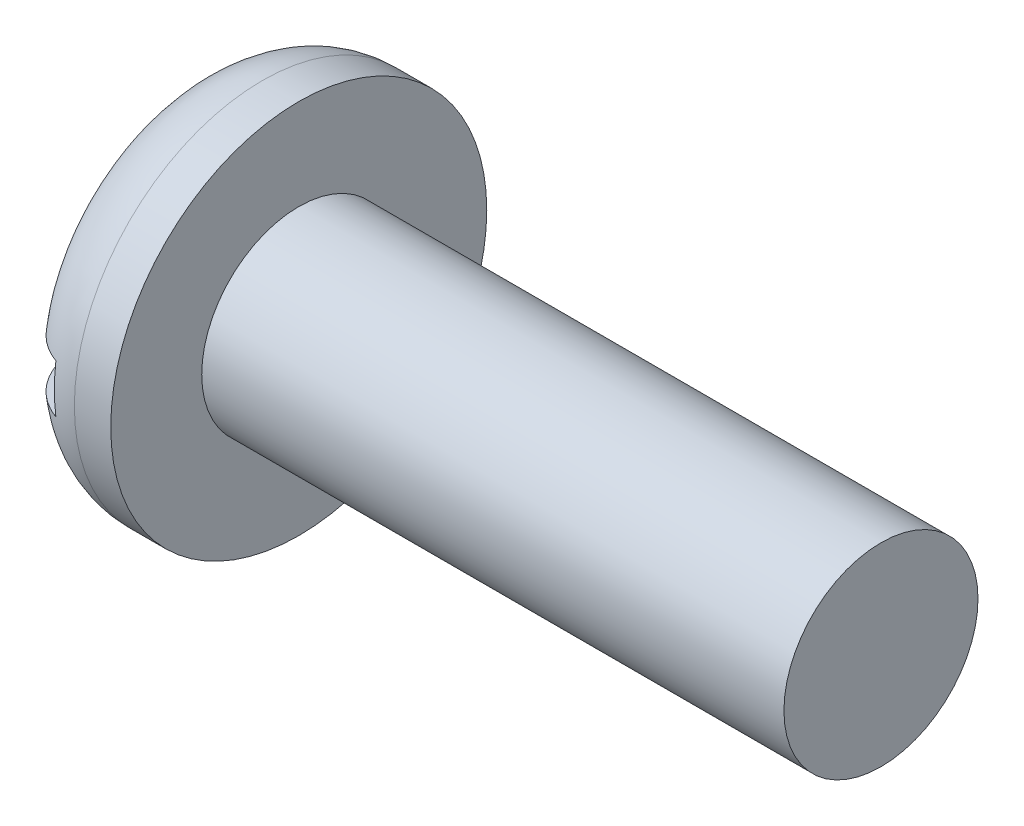
SolidWorks part; units mm, degrees
ref_plane "Front Plane" through (0, 0, 0) normal (0, 0, 1) x (1, 0, 0)
ref_plane "Top Plane" through (0, 0, 0) normal (0, 1, 0) x (1, 0, 0)
ref_plane "Right Plane" through (0, 0, 0) normal (1, 0, 0) x (0, 0, -1)
sketch "Sketch1" plane through (0, 0, 0) normal (0, 0, 1) x (1, 0, 0)
  line L0 (0, 0) -> (-5.157, 0) construction
  line L1 (0, 0) -> (14.25, 0)
  line L2 (14.25, 0) -> (14.25, 2)
  line L3 (14.25, 2) -> (2.25, 2)
  line L4 (2.25, 2) -> (2.25, 3.875)
  line L5 (2.25, 3.875) -> (1.5, 3.875)
  line L6 (0, 2.375) -> (0, 0)
  arc A0 (1.5, 3.875) -> (0, 2.375) centre (1.5, 2.375) ccw
  dimension "D1" = 7.75
  dimension "D2" = 4
  dimension "D3" = 12
  dimension "D4" = 2.25
  dimension "D5" = 1.5
revolve "Revolve1" add sketch "Sketch1" angle 360 about L0
sketch "Sketch2" plane through (0, 0, 0) normal (-1, 0, 0) x (0, 0, 1)
  line L1 (-6.095, -0.5) -> (6.095, -0.5)
  line L2 (-6.095, -0.5) -> (-6.095, 0.5)
  line L3 (-6.095, 0.5) -> (6.095, 0.5)
  line L4 (6.095, -0.5) -> (6.095, 0.5)
  line L5 (-6.095, -0.5) -> (6.095, 0.5) construction
  line L6 (-6.095, 0.5) -> (6.095, -0.5) construction
  point P0 (0, 0)
  dimension "D1" = 1
extrude "Cut-Extrude1" cut sketch "Sketch2" against normal blind 1
